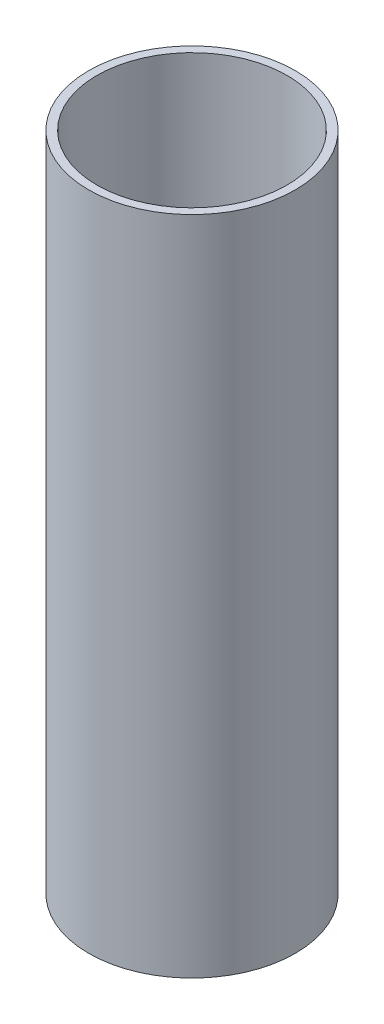
SolidWorks part; units mm, degrees
ref_plane "Front Plane" through (0, 0, 0) normal (0, 0, 1) x (1, 0, 0)
ref_plane "Top Plane" through (0, 0, 0) normal (0, 1, 0) x (1, 0, 0)
ref_plane "Right Plane" through (0, 0, 0) normal (1, 0, 0) x (0, 0, -1)
sketch "Sketch1" plane through (0, 0, 0) normal (0, 1, 0) x (1, 0, 0)
  circle A0 centre (0, 0) radius 11.5
  circle A1 centre (0, 0) radius 12.5
  dimension "D1" = 23
  dimension "D2" = 25
extrude "Boss-Extrude1" add sketch "Sketch1" along normal blind 80
